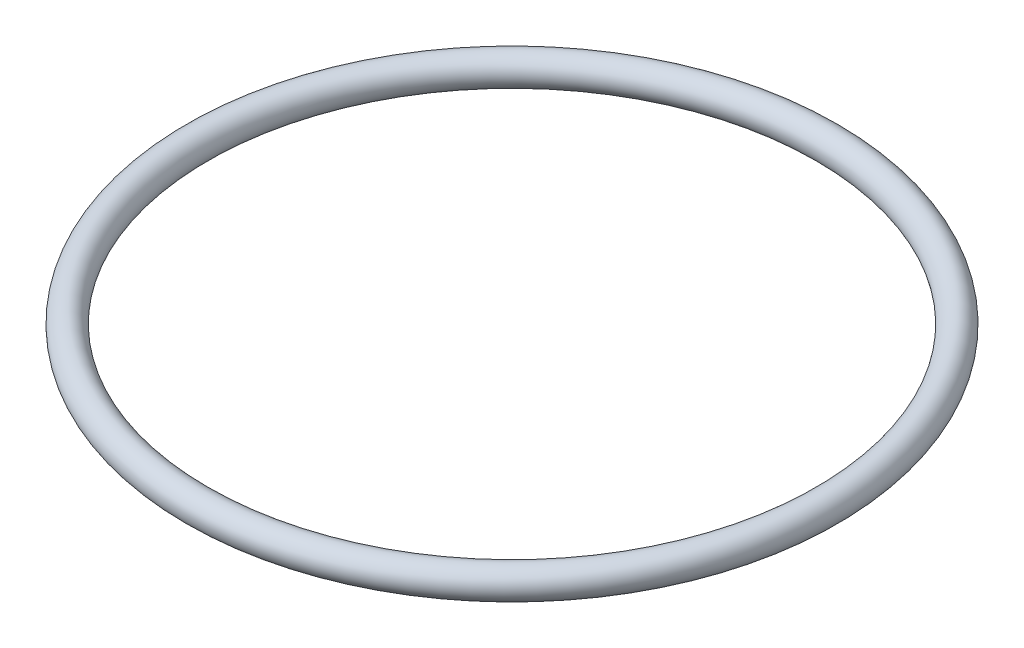
SolidWorks part; units mm, degrees
ref_plane "Front Plane" through (0, 0, 0) normal (0, 0, 1) x (1, 0, 0)
ref_plane "Top Plane" through (0, 0, 0) normal (0, 1, 0) x (1, 0, 0)
ref_plane "Right Plane" through (0, 0, 0) normal (1, 0, 0) x (0, 0, -1)
sketch "Sketch2" plane through (0, 0, 0) normal (0, 0, 1) x (1, 0, 0)
  line L0 (0, 0) -> (0, 22.5506) construction
  circle A0 centre (21, 0) radius 1
  dimension "D3" = 2
  dimension "D1" = 22.5506
  dimension "D2" = 21
revolve "Revolve1" add sketch "Sketch2" angle 360 about L0
sketch "Sketch3" plane through (0, 0, 0) normal (0, 1, 0) x (1, 0, 0)
  circle A0 centre (0, 0) radius 20.5
  dimension "D1" = 41
